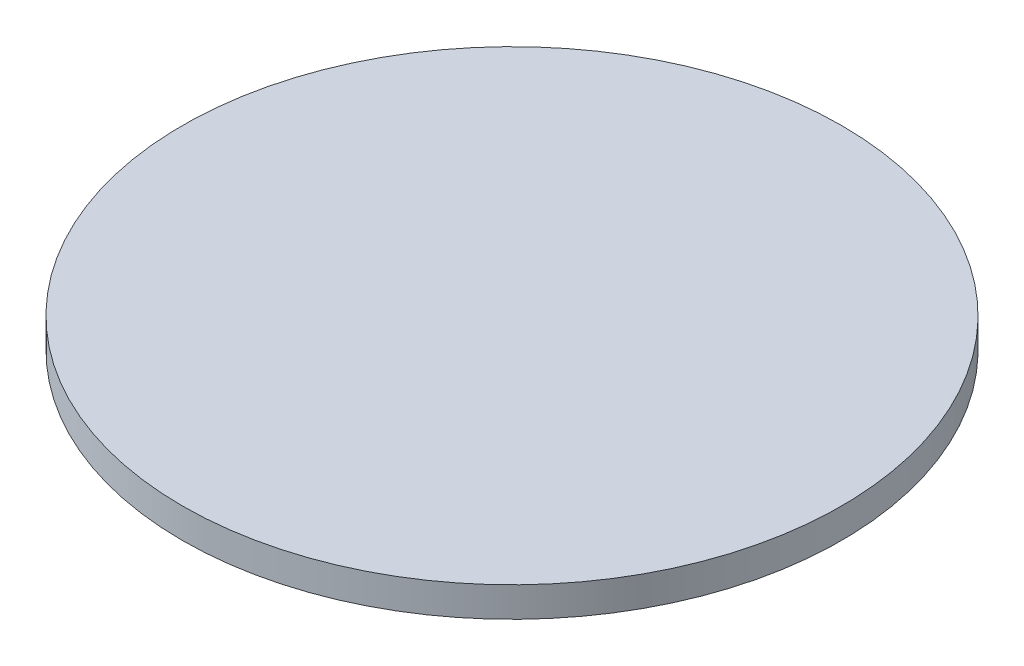
SolidWorks part; units mm, degrees
ref_plane "Front Plane" through (0, 0, 0) normal (0, 0, 1) x (1, 0, 0)
ref_plane "Top Plane" through (0, 0, 0) normal (0, 1, 0) x (1, 0, 0)
ref_plane "Right Plane" through (0, 0, 0) normal (1, 0, 0) x (0, 0, -1)
sketch "Sketch1" plane through (0, 0, 0) normal (0, 1, 0) x (1, 0, 0)
  circle A0 centre (0, 0) radius 2.9369
  dimension "D1" = 5.8738
extrude "cap" add sketch "Sketch1" along normal blind 0.2666
equation "\"magnet_inset\"= 0.0625in"
equation "\"magnet_diameter\"= 0.2in"
equation "\"steel_inset_distance\"= 1in / 32"
equation "\"kapton_thickness\"= 0.005in"
equation "\"pcb_thickness\"= 0.6mm"
equation "\"magnet_thickness\"= 0.03125in"
equation "\"D1@Sketch1\"=(\"magnet_diameter\") + (\"steel_inset_distance\")"
equation "\"D1@cap\"=( \"pcb_thickness\"+\"kapton_thickness\"/2)-(\"magnet_thickness\"/2)"
equation "\"edge_radius\"= 1in / 10"
equation "\"card_width\"= 78mm"
equation "\"card_height\"= 50mm"
equation "\"battery_diameter\"= 20mm"
equation "\"battery_oversize\"= 0.1mm"
equation "\"battery_vertical_inset\"= 1in / 16"
equation "\"battery_horizontal_inset\"= 1in / 4"
equation "\"battery_spacing\"= 1in / 16"
equation "\"battery_thickness\"= 1.6mm"
